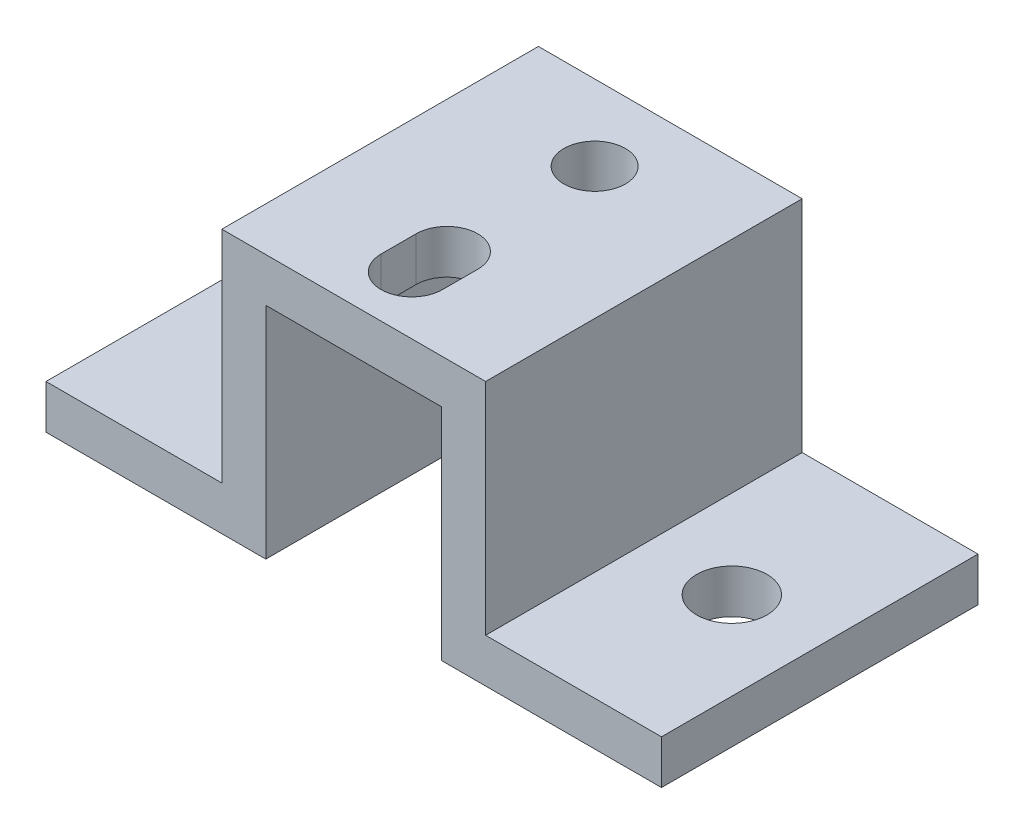
SolidWorks part; units mm, degrees
ref_plane "Plano frontal" through (0, 0, 0) normal (0, 0, 1) x (1, 0, 0)
ref_plane "Plano superior" through (0, 0, 0) normal (0, 1, 0) x (1, 0, 0)
ref_plane "Plano direito" through (0, 0, 0) normal (1, 0, 0) x (0, 0, -1)
sketch "Esboço1" plane through (0, 0, 0) normal (0, 0, 1) x (1, 0, 0)
  line L0 (-35, 0) -> (-25, 0)
  line L1 (-25, 0) -> (-25, 12.5)
  line L2 (-25, 12.5) -> (-10, 12.5)
  line L3 (-10, 12.5) -> (-10, 0)
  line L4 (-10, 0) -> (0, 0)
  line L5 (-35, -2.5) -> (-22.5, -2.5)
  line L6 (-22.5, -2.5) -> (-22.5, 10)
  line L7 (-22.5, 10) -> (-12.5, 10)
  line L8 (-12.5, 10) -> (-12.5, -2.5)
  line L9 (-12.5, -2.5) -> (0, -2.5)
  line L10 (-10, 0) -> (82.3751, 0) construction
  line L11 (-12.5, -2.5) -> (82.3751, -2.5) construction
  line L12 (0, 0) -> (0, -2.5)
  line L13 (-35, -2.5) -> (-35, 0)
  dimension "D2" = 10
  dimension "D3" = 15
  dimension "D4" = 10
  dimension "D1" = 2.5
extrude "Ressalto-extrusão1" add sketch "Esboço1" along normal blind 18
sketch "Esboço2" plane through (0, 12.5, 0) normal (0, 1, 0) x (1, 0, 0)
  line L0 (-17.5, -14.7) -> (-17.5, -12.7) construction
  line L1 (-19.25, -14.7) -> (-19.25, -12.7)
  line L2 (-15.75, -14.7) -> (-15.75, -12.7)
  line L3 (-17.5, -4.3) -> (-17.5, -13.7) construction
  line L4 (-25, -18) -> (-25, 0) construction
  line L5 (-25, -18) -> (-35, -18) construction
  line L6 (-10, 0) -> (-25, 0) construction
  circle A0 centre (-17.5, -4.3) radius 1.75
  arc A1 (-19.25, -14.7) -> (-15.75, -14.7) centre (-17.5, -14.7) ccw
  arc A2 (-15.75, -12.7) -> (-19.25, -12.7) centre (-17.5, -12.7) ccw
  circle A3 centre (-30, -9) radius 2
  circle A4 centre (-5, -9) radius 2
  point P4 (-17.5, -13.7)
  point P12 (-25, -9)
  point P13 (-17.5, -9)
  point P20 (-30, -18)
  point P24 (-17.5, 0)
  dimension "D2" = 3.5
  dimension "D4" = 4
  dimension "D1" = 2
  dimension "D3" = 9.4
extrude "Corte-extrusão1" cut sketch "Esboço2" against normal through all
